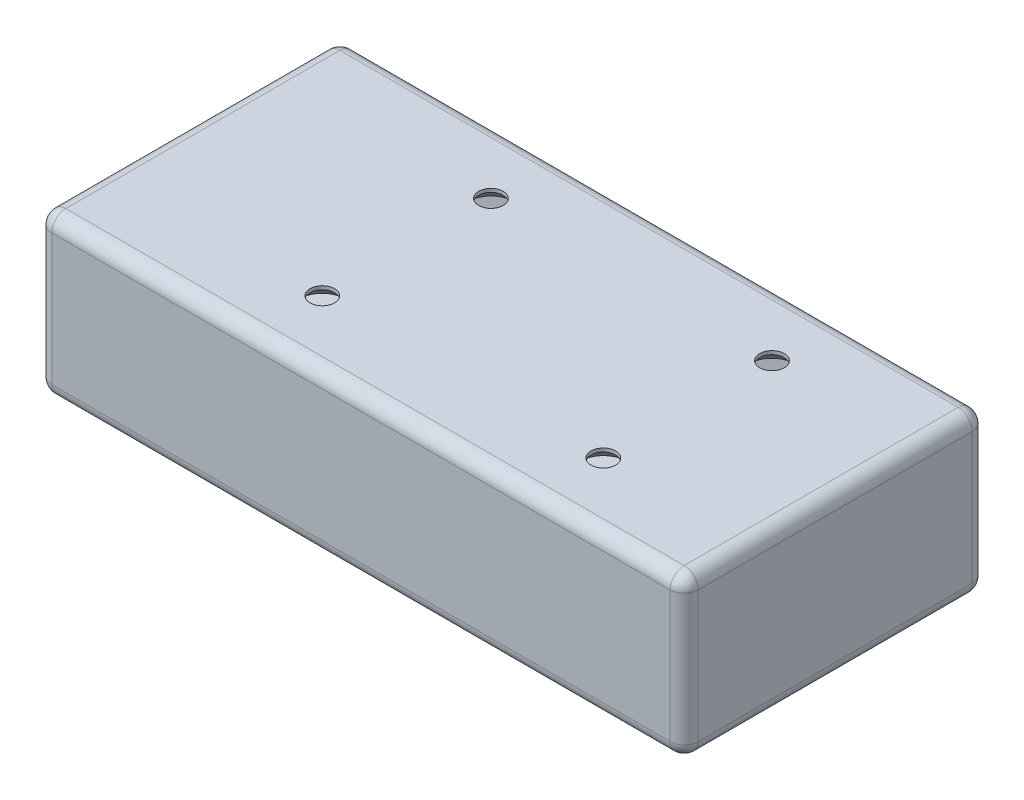
SolidWorks part; units mm, degrees
ref_plane "Front Plane" through (0, 0, 0) normal (0, 0, 1) x (1, 0, 0)
ref_plane "Top Plane" through (0, 0, 0) normal (0, 1, 0) x (1, 0, 0)
ref_plane "Right Plane" through (0, 0, 0) normal (1, 0, 0) x (0, 0, -1)
sketch "Sketch1" plane through (0, 0, 0) normal (0, 1, 0) x (1, 0, 0)
  line L1 (46, -21.5) -> (-46, -21.5)
  line L2 (46, -21.5) -> (46, 21.5)
  line L3 (46, 21.5) -> (-46, 21.5)
  line L4 (-46, -21.5) -> (-46, 21.5)
  line L5 (46, -21.5) -> (-46, 21.5) construction
  line L6 (46, 21.5) -> (-46, -21.5) construction
  point P0 (0, 0)
  dimension "D1" = 92
  dimension "D2" = 43
extrude "Boss-Extrude1" add sketch "Sketch1" along normal blind 22.7
shell "Shell1" thickness 2
fillet "Fillet1" radius 2 12 edges at (0, 0, -21.5) (-46, 11.35, -21.5) (-46, 0, 0) (-46, 11.35, 21.5) (0, 0, 21.5) (46, 11.35, 21.5) (46, 11.35, -21.5) (46, 0, 0) (0, 22.7, -21.5) (46, 22.7, 0) (0, 22.7, 21.5) (-46, 22.7, 0)
sketch "Sketch2" plane through (0, 22.7, 0) normal (0, 1, 0) x (1, 0, 0)
  circle A0 centre (-15, 12) radius 1.75
  circle A1 centre (-15, -12) radius 1.75
  circle A2 centre (25, -12) radius 1.75
  circle A3 centre (25, 12) radius 1.75
  dimension "D5" = 3.5
  dimension "D1" = 25
  dimension "D2" = 40
  dimension "D3" = 12
  dimension "D4" = 24
extrude "Cut-Extrude1" cut sketch "Sketch2" against normal blind 10
sketch "Sketch3" plane through (-46, 0, 0) normal (-1, 0, 0) x (0, 0, 1)
  line L0 (-19.5, 22.7) -> (19.5, 22.7) construction
  line L1 (21.5, 20.7) -> (21.5, 2) construction
  circle A0 centre (15.5, 17.7) radius 2
  dimension "D3" = 4
  dimension "D1" = 5
  dimension "D2" = 6
extrude "Cut-Extrude2" cut sketch "Sketch3" against normal blind 1
sketch "Sketch4" plane through (-45, 0, 0) normal (-1, 0, 0) x (0, 0, 1)
  circle A0 centre (14.4969, 17.7504) radius 0.7
  dimension "D1" = 1.4
ref_plane "Plane1" through (0, 0, 14.4969) normal (0, 0, 1) x (1, 0, 0)
sketch "Sketch5" plane through (0, 0, 14.4969) normal (0, 0, 1) x (1, 0, 0)
  line L0 (-45, 18.4504) -> (-45, 17.0504) construction
  spline S0 degree 3 poles (-45, 17.7504) (-51.2015, 17.2731) (-57.4864, 22.7915) (-57.2689, 29.1383) knots 0 0 0 0 1 1 1 1
sweep "Sweep1" [suppressed] add profiles "Sketch4" path "Sketch5"
sketch "Sketch6" plane through (-46, 0, 0) normal (-1, 0, 0) x (0, 0, 1)
  line L0 (-19.5, 22.7) -> (19.5, 22.7) construction
  line L1 (-12.5, 12.7) -> (-4.5, 12.7)
  line L2 (-12.5, 12.7) -> (-12.5, 7.7)
  line L3 (-12.5, 7.7) -> (-4.5, 7.7)
  line L4 (-4.5, 12.7) -> (-4.5, 7.7)
  line L5 (-21.5, 2) -> (-21.5, 20.7) construction
  dimension "D1" = 8
  dimension "D2" = 5
  dimension "D3" = 10
  dimension "D4" = 9
extrude "Cut-Extrude3" cut sketch "Sketch6" against normal blind 1
sketch "Sketch7" plane through (-45, 0, 0) normal (-1, 0, 0) x (0, 0, 1)
  line L1 (-11.3717, 10.9496) -> (-8.2863, 10.9496)
  line L2 (-11.3717, 10.9496) -> (-11.3717, 9.1425)
  line L3 (-11.3717, 9.1425) -> (-8.2863, 9.1425)
  line L4 (-8.2863, 10.9496) -> (-8.2863, 9.1425)
extrude "Boss-Extrude2" add sketch "Sketch7" along normal blind 4
pattern_linear "LPattern1" [suppressed] count 2 spacing 2
chamfer "Chamfer1" distance 1.5 angle 45 4 edges at (-15, 20.7, -10.25) (25, 20.7, -10.25) (25, 20.7, 13.75) (-15, 20.7, 13.75)
